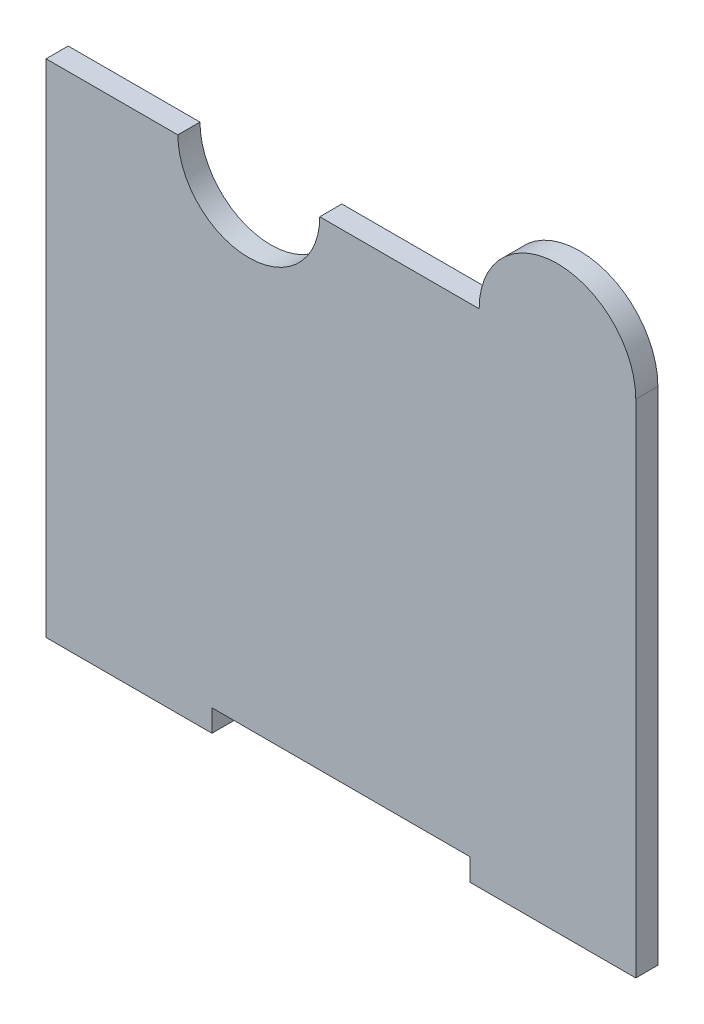
SolidWorks part; units mm, degrees
ref_plane "Front Plane" through (0, 0, 0) normal (0, 0, 1) x (1, 0, 0)
ref_plane "Top Plane" through (0, 0, 0) normal (0, 1, 0) x (1, 0, 0)
ref_plane "Right Plane" through (0, 0, 0) normal (1, 0, 0) x (0, 0, -1)
sketch "Sketch1" plane through (0, 0, 0) normal (0, 0, 1) x (1, 0, 0)
  line L0 (-55, 0) -> (-19.25, 0)
  line L2 (105, 0) -> (105, -136)
  line L3 (60, -130) -> (-10, -130)
  line L7 (-55, -136) -> (-10, -136)
  line L8 (-10, -130) -> (-10, -136)
  line L15 (105, -136) -> (60, -136)
  line L16 (60, -130) -> (60, -136)
  line L17 (-55, 0) -> (-55, -136)
  line L18 (19.25, 0) -> (62.5, 0)
  arc A1 (105, 0) -> (62.5, 0) centre (83.75, 0) ccw
  arc A2 (-19.25, 0) -> (19.25, 0) centre (0, 0) ccw
  dimension "D3" = 38.5
  dimension "D2" = 105
  dimension "D4" = 45
  dimension "D5" = 6
  dimension "D7" = 6
  dimension "D8" = 45
extrude "Boss-Extrude1" add sketch "Sketch1" along normal blind 6
